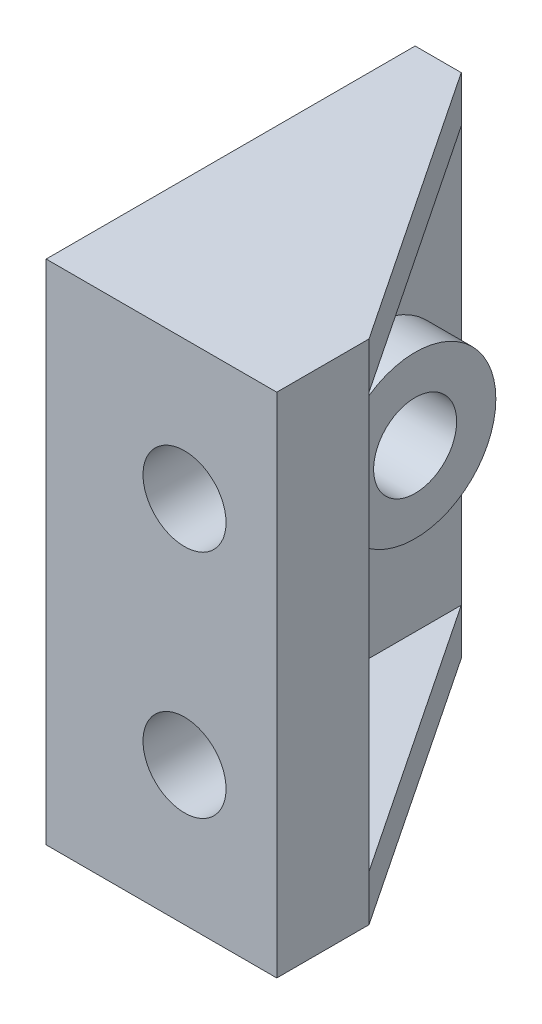
SolidWorks part; units mm, degrees
material "ABS"
ref_plane "Спереди" through (0, 0, 0) normal (0, 0, 1) x (1, 0, 0)
ref_plane "Сверху" through (0, 0, 0) normal (0, 1, 0) x (1, 0, 0)
ref_plane "Справа" through (0, 0, 0) normal (1, 0, 0) x (0, 0, -1)
sketch "Sketch1" plane through (0, 0, 0) normal (0, 1, 0) x (1, 0, 0)
  line L0 (0, 0) -> (0, -40)
  line L1 (0, -40) -> (25, -40)
  line L2 (25, -40) -> (25, -30)
  line L3 (5, 0) -> (0, 0)
  line L4 (25, -30) -> (5, 0)
  dimension "D1" = 25
  dimension "D2" = 40
  dimension "D3" = 5
  dimension "D4" = 10
extrude "Boss-Extrude1" add sketch "Sketch1" along normal blind 55
sketch "Sketch7" plane through (25, 0, 0) normal (1, 0, 0) x (0, 0, -1)
  line L0 (-30, 55) -> (-30, 0) construction
  line L1 (-30, 50) -> (0, 50)
  line L2 (-30, 50) -> (-30, 5)
  line L3 (-30, 5) -> (0, 5)
  line L4 (0, 50) -> (0, 5)
  line L5 (0, 55) -> (0, 0) construction
  line L6 (-30, 55) -> (0, 55) construction
  line L7 (-30, 0) -> (0, 0) construction
  dimension "D1" = 5
  dimension "D2" = 5
extrude "Cut-Extrude5" cut sketch "Sketch7" against normal blind 20
sketch "Sketch6" plane through (0, 0, 40) normal (0, 0, 1) x (1, 0, 0)
  line L0 (0, 55) -> (0, 0) construction
  line L1 (0, 55) -> (25, 55) construction
  circle A0 centre (15, 40) radius 4.5
  circle A1 centre (15, 15) radius 4.5
  dimension "D1" = 9
  dimension "D3" = 25
  dimension "D4" = 15
  dimension "D5" = 15
extrude "Cut-Extrude4" cut sketch "Sketch6" against normal up to next
sketch "Sketch8" plane through (5, 0, 0) normal (1, 0, 0) x (0, 0, -1)
  line L0 (-30, 55) -> (0, 55) construction
  line L1 (0, 5) -> (0, 50) construction
  circle A0 centre (-10, 27.5) radius 8.75
  dimension "D1" = 17.5
  dimension "D2" = 27.5
  dimension "D3" = 10
extrude "Boss-Extrude2" add sketch "Sketch8" along normal blind 5
sketch "Sketch9" plane through (10, 0, 0) normal (1, 0, 0) x (0, 0, -1)
  circle A0 centre (-10, 27.5) radius 4.5
  dimension "D1" = 9
extrude "Cut-Extrude6" cut sketch "Sketch9" against normal up to next
